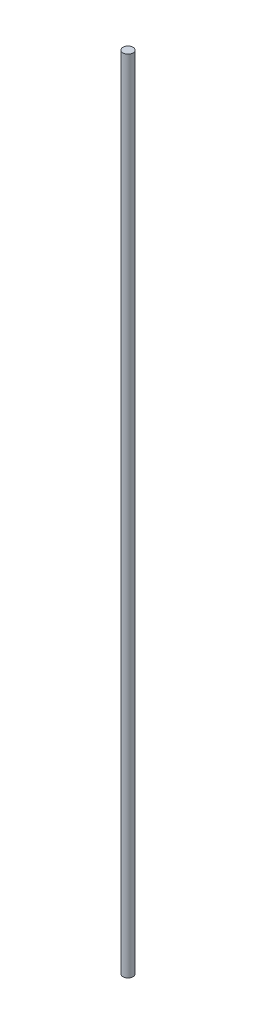
SolidWorks part; units mm, degrees
material "Thornel Mat VMA"
ref_plane "前视基准面" through (0, 0, 0) normal (0, 0, 1) x (1, 0, 0)
ref_plane "上视基准面" through (0, 0, 0) normal (0, 1, 0) x (1, 0, 0)
ref_plane "右视基准面" through (0, 0, 0) normal (1, 0, 0) x (0, 0, -1)
sketch "草图1" plane through (0, 0, 0) normal (0, 1, 0) x (1, 0, 0)
  circle A0 centre (0, 0) radius 1
  dimension "D1" = 2
extrude "凸台-拉伸1" add sketch "草图1" along normal blind 160
equation "\"m\"= 2"
